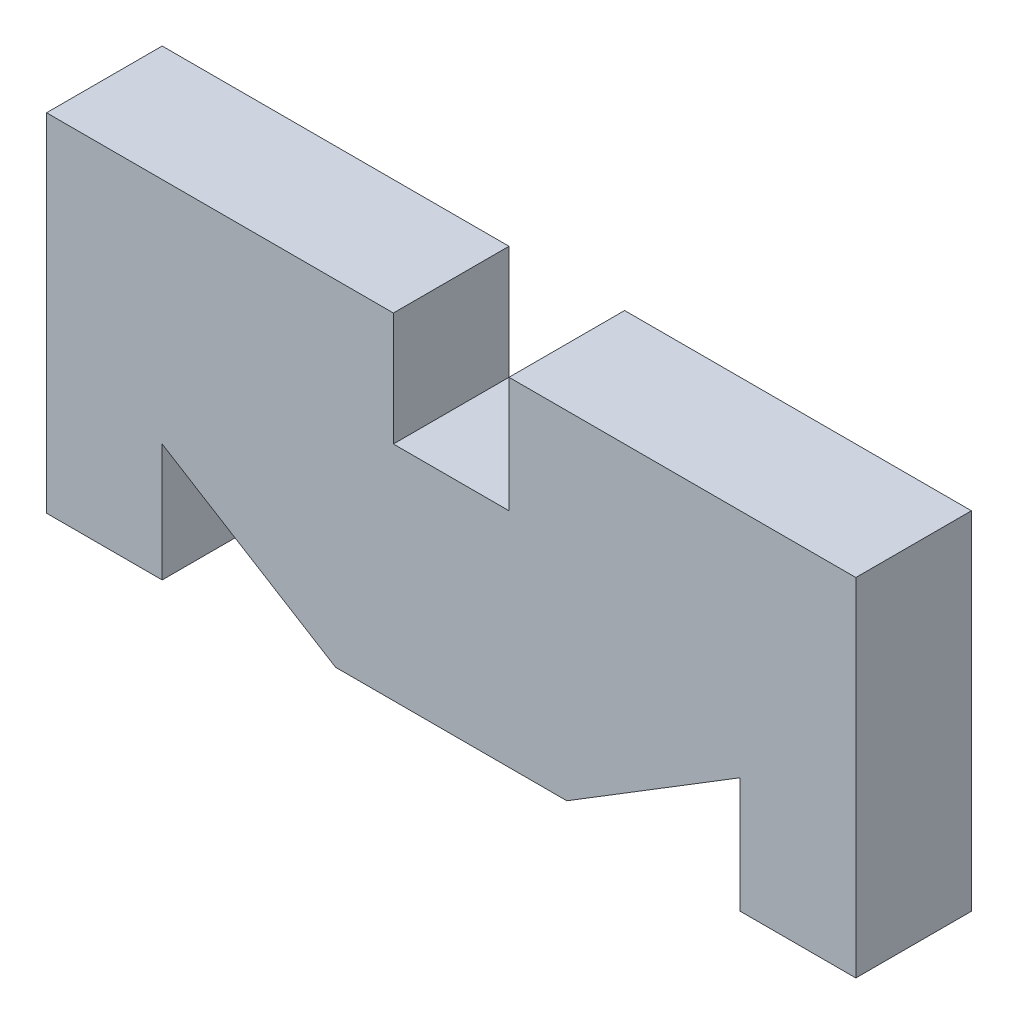
SolidWorks part; units mm, degrees
ref_plane "Front Plane" through (0, 0, 0) normal (0, 0, 1) x (1, 0, 0)
ref_plane "Top Plane" through (0, 0, 0) normal (0, 1, 0) x (1, 0, 0)
ref_plane "Right Plane" through (0, 0, 0) normal (1, 0, 0) x (0, 0, -1)
sketch "Sketch2" plane through (0, 0, 0) normal (0, 0, 1) x (1, 0, 0)
  line L0 (1.8485, 23.7187) -> (31.8485, 23.7187)
  line L1 (31.8485, 23.7187) -> (31.8485, 13.9041)
  line L2 (31.8485, 13.9041) -> (41.8485, 13.9041)
  line L3 (41.8485, 13.9041) -> (41.8485, 23.9041)
  line L4 (41.8485, 23.9041) -> (71.8485, 23.9041)
  line L5 (71.8485, 23.9041) -> (71.8485, -6.0959)
  line L6 (71.8485, -6.0959) -> (61.8485, -6.0959)
  line L7 (61.8485, -6.0959) -> (61.8485, 3.9041)
  line L8 (61.8485, 3.9041) -> (46.8485, -5.3216)
  line L9 (46.8485, -5.3216) -> (26.8485, -5.3216)
  line L10 (26.8485, -5.3216) -> (11.8485, 3.9041)
  line L11 (11.8485, 3.9041) -> (11.8485, -6.2813)
  line L12 (11.8485, -6.2813) -> (1.8485, -6.2813)
  line L13 (1.8485, -6.2813) -> (1.8485, 23.7187)
  dimension "D1" = 30
  dimension "D2" = 30
  dimension "D3" = 10
  dimension "D4" = 30
  dimension "D5" = 10
  dimension "D6" = 30
  dimension "D7" = 10
  dimension "D8" = 10
  dimension "D9" = 15
  dimension "D10" = 20
  dimension "D11" = 15
extrude "Boss-Extrude1" add sketch "Sketch2" along normal blind 10
